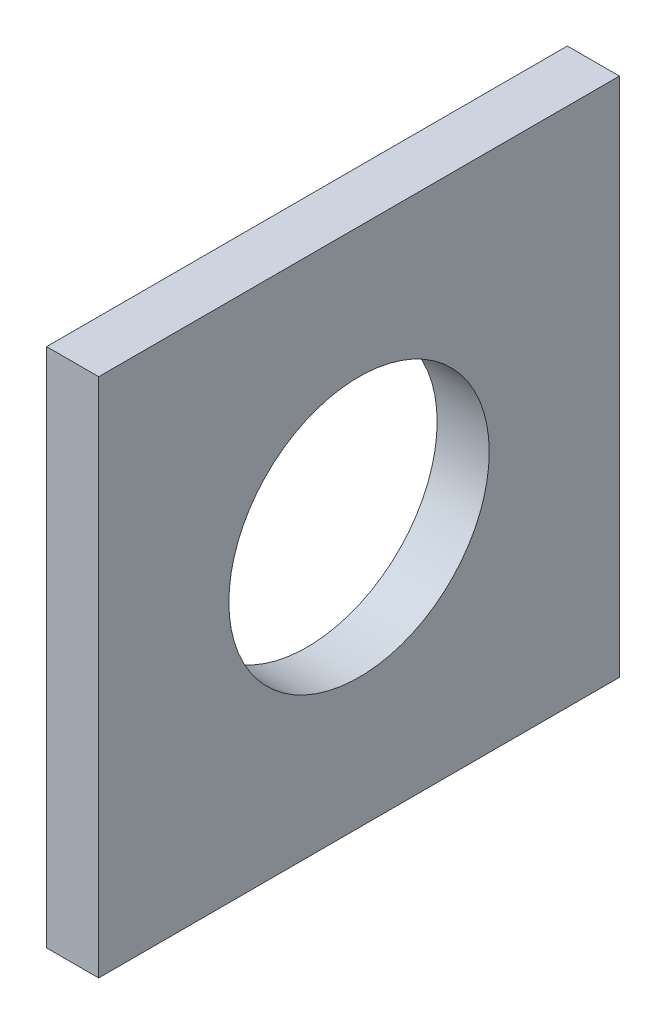
SolidWorks part; units mm, degrees
ref_plane "Front Plane" through (0, 0, 0) normal (0, 0, 1) x (1, 0, 0)
ref_plane "Top Plane" through (0, 0, 0) normal (0, 1, 0) x (1, 0, 0)
ref_plane "Right Plane" through (0, 0, 0) normal (1, 0, 0) x (0, 0, -1)
sketch "Sketch1" plane through (0, 0, 0) normal (1, 0, 0) x (0, 0, -1)
  line L1 (0, 0) -> (20, 0)
  line L2 (0, 0) -> (0, 20)
  line L3 (0, 20) -> (20, 20)
  line L4 (20, 0) -> (20, 20)
  dimension "D1" = 20
  dimension "D2" = 20
extrude "Boss-Extrude1" add sketch "Sketch1" along normal blind 2
sketch "Sketch2" plane through (2, 0, 0) normal (1, 0, 0) x (0, 0, -1)
  line L1 (20, 20) -> (0, 20) construction
  line L2 (20, 0) -> (20, 20) construction
  circle A0 centre (10, 10) radius 5
  point P4 (0, 0)
  point P6 (0, 0)
  dimension "D1" = 10
  dimension "D2" = 10
  dimension "D3" = 10
extrude "Cut-Extrude1" cut sketch "Sketch2" against normal through all
